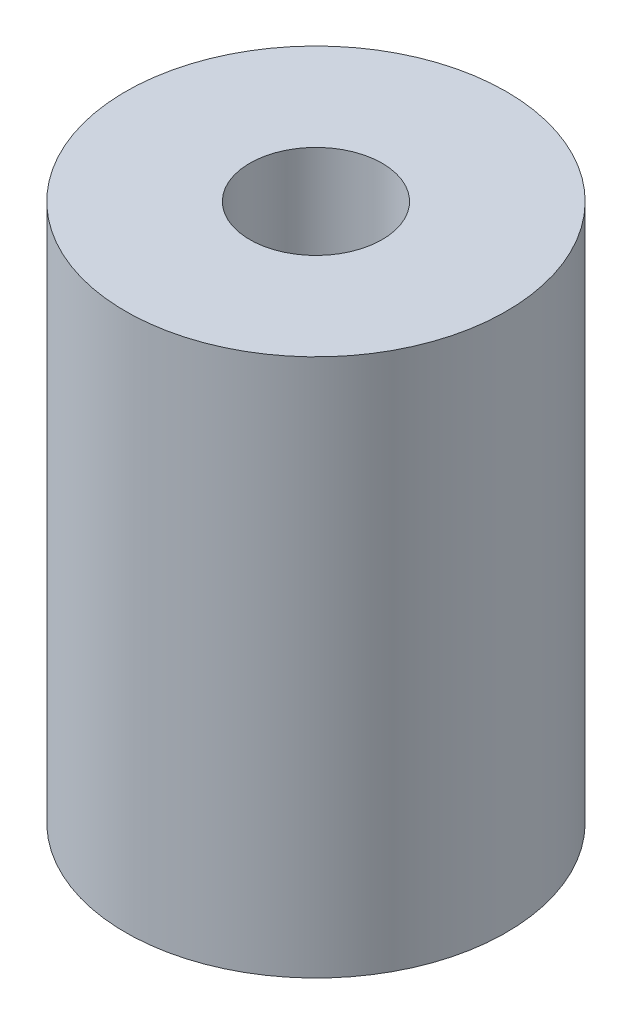
SolidWorks part; units mm, degrees
ref_plane "Front Plane" through (0, 0, 0) normal (0, 0, 1) x (1, 0, 0)
ref_plane "Top Plane" through (0, 0, 0) normal (0, 1, 0) x (1, 0, 0)
ref_plane "Right Plane" through (0, 0, 0) normal (1, 0, 0) x (0, 0, -1)
sketch "Sketch1" plane through (0, 0, 0) normal (0, 1, 0) x (1, 0, 0)
  circle A0 centre (0, 0) radius 1.6
  circle A1 centre (0, 0) radius 4.6
  dimension "D1" = 3.2
  dimension "D2" = 3
extrude "Boss-Extrude1" add sketch "Sketch1" along normal blind 13
